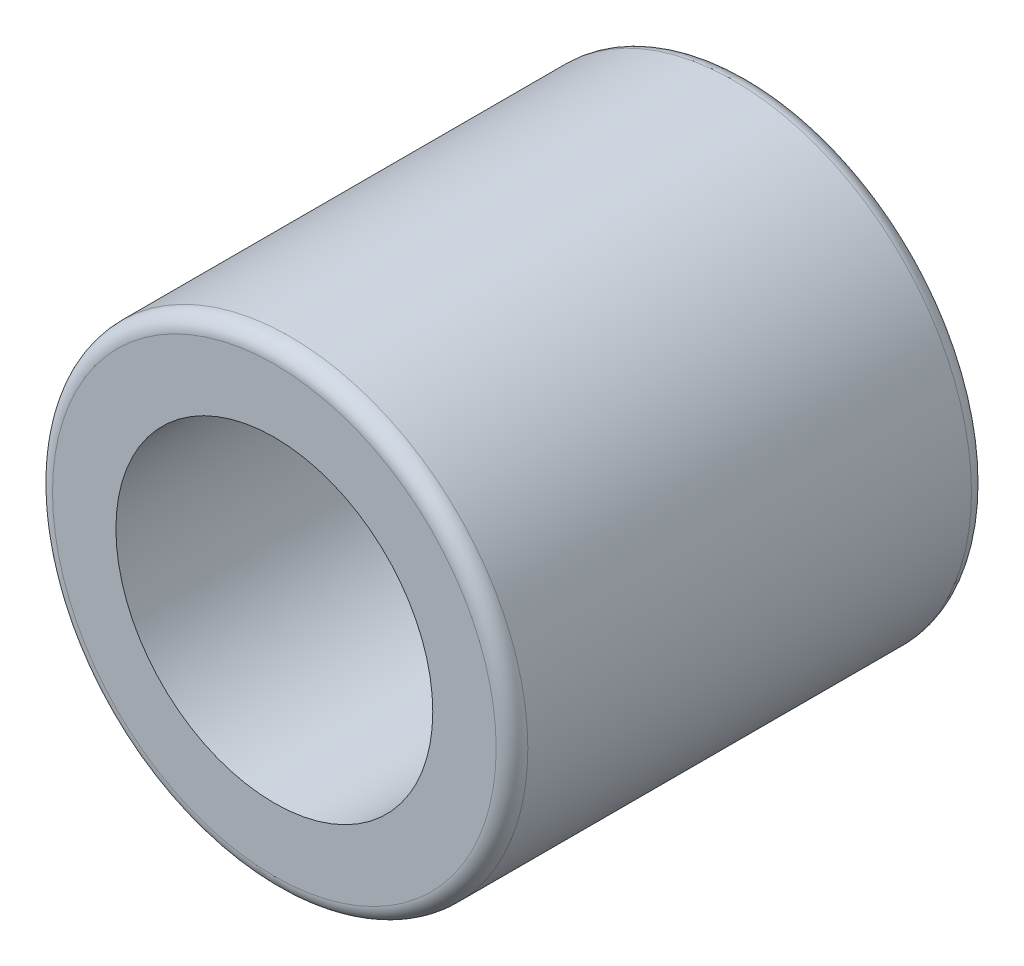
SolidWorks part; units mm, degrees
material "Kurşunlu Ticari Bronz"
ref_plane "Ön Düzlem" through (0, 0, 0) normal (0, 0, 1) x (1, 0, 0)
ref_plane "Üst Düzlem" through (0, 0, 0) normal (0, 1, 0) x (1, 0, 0)
ref_plane "Sağ Düzlem" through (0, 0, 0) normal (1, 0, 0) x (0, 0, -1)
sketch "Çizim3" plane through (0, 0, 0) normal (0, 0, 1) x (1, 0, 0)
  circle A0 centre (0, 0) radius 15
  circle A1 centre (0, 0) radius 10
  dimension "D1" = 30
  dimension "D2" = 20
extrude "Yükseklik-Ekstrüzyon1" add sketch "Çizim3" along normal mid plane 30
fillet "Radyus1" radius 1 2 edges at (15, 0, -15) (15, 0, 15)
